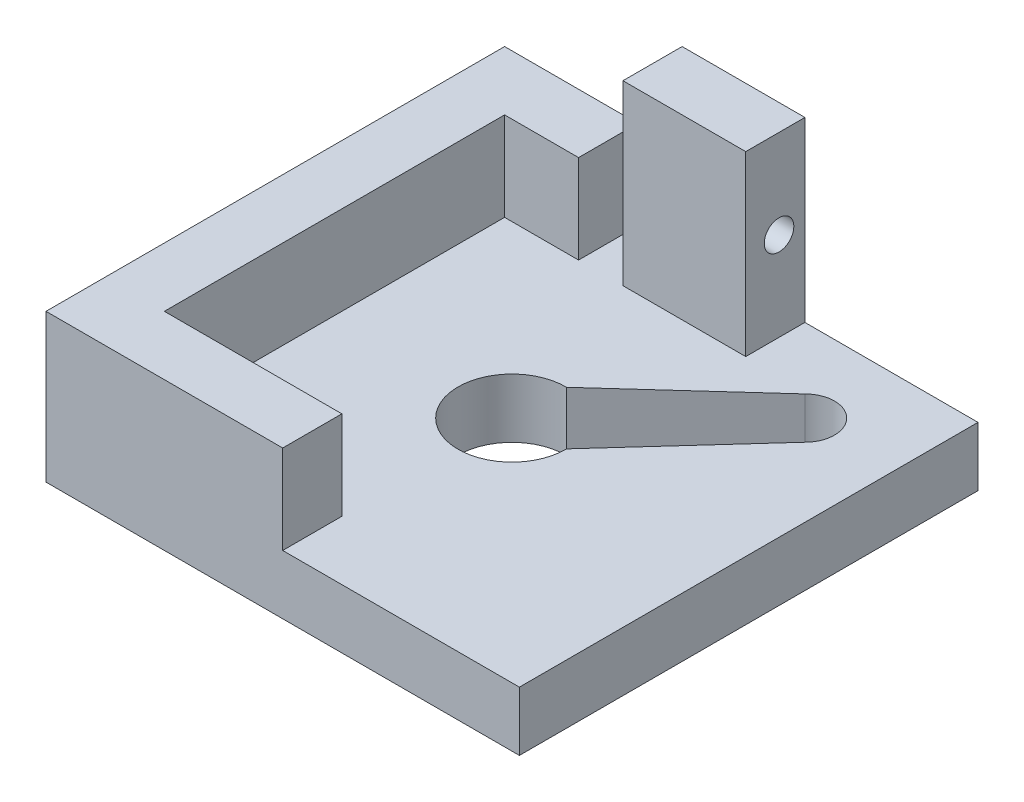
SolidWorks part; units mm, degrees
ref_plane "Front Plane" through (0, 0, 0) normal (0, 0, 1) x (1, 0, 0)
ref_plane "Top Plane" through (0, 0, 0) normal (0, 1, 0) x (1, 0, 0)
ref_plane "Right Plane" through (0, 0, 0) normal (1, 0, 0) x (0, 0, -1)
sketch "Sketch1" plane through (0, 0, 0) normal (0, 1, 0) x (1, 0, 0)
  line L1 (-16, -15.5) -> (16, -15.5)
  line L2 (-16, -15.5) -> (-16, 15.5)
  line L3 (-16, 15.5) -> (16, 15.5)
  line L4 (16, -15.5) -> (16, 15.5)
  line L5 (-16, -15.5) -> (16, 15.5) construction
  line L6 (-16, 15.5) -> (16, -15.5) construction
  point P0 (0, 0)
  dimension "D1" = 32
  dimension "D2" = 31
extrude "Boss-Extrude1" add sketch "Sketch1" along normal blind 4
sketch "Sketch2" plane through (0, 4, 0) normal (0, 1, 0) x (1, 0, 0)
  line L0 (-16, 15.5) -> (-16, -15.5)
  line L1 (-16, -15.5) -> (0, -15.5)
  line L2 (-16, -15.5) -> (16, -15.5) construction
  line L3 (0, -15.5) -> (0, -11.5)
  line L7 (-7, 11.5) -> (-12, 11.5)
  line L8 (-12, 11.5) -> (-12, -11.5)
  line L9 (-12, -11.5) -> (0, -11.5)
  line L10 (-16, 15.5) -> (-7, 15.5)
  line L11 (16, 15.5) -> (-16, 15.5) construction
  line L12 (-7, 15.5) -> (-7, 11.5)
  dimension "D1" = 4
  dimension "D2" = 4
  dimension "D3" = 5
  dimension "D4" = 4
  dimension "D5" = 31
  dimension "D6" = 9
  dimension "D7" = 16
extrude "Boss-Extrude2" add sketch "Sketch2" along normal blind 6
sketch "Sketch5" plane through (0, 4, 0) normal (0, 1, 0) x (1, 0, 0)
  line L0 (16, 15.5) -> (-7, 15.5) construction
  line L1 (-4, 11.5) -> (4.3, 11.5)
  line L2 (-4, 11.5) -> (-4, 15.5)
  line L3 (-4, 15.5) -> (4.3, 15.5)
  line L4 (4.3, 11.5) -> (4.3, 15.5)
  line L5 (-7, 11.5) -> (-7, 15.5) construction
  dimension "D1" = 3
  dimension "D2" = 8.3
  dimension "D3" = 4
extrude "Boss-Extrude3" add sketch "Sketch5" along normal blind 12
sketch "Sketch6" plane through (4.3, 0, 0) normal (1, 0, 0) x (0, 0, -1)
  line L0 (11.5, 16) -> (11.5, 4) construction
  line L2 (11.5, 16) -> (15.5, 16) construction
  circle A0 centre (13.75, 10) radius 1
  point P4 (0, 0)
  point P6 (13.7608, 16)
  dimension "D1" = 2
  dimension "D2" = 2.25
  dimension "D3" = 6
extrude "Cut-Extrude7" cut sketch "Sketch6" against normal blind 5
sketch "Sketch4" plane through (0, 4, 0) normal (0, 1, 0) x (0.7071, 0, -0.7071)
  line L0 (0, 0) -> (0, 2.55) construction
  line L1 (0, 0) -> (0, -2.55) construction
  line L2 (0, 0) -> (16, 0) construction
  line L4 (0, -2.55) -> (2.6115, -2.55) construction
  line L5 (2.6115, 2.55) -> (14, 2)
  line L7 (0, 2.55) -> (2.6115, 2.55) construction
  line L10 (16, 0) -> (14, 2) construction
  line L11 (16, 0) -> (14, -2) construction
  line L12 (2.6115, -2.55) -> (14, -2)
  circle A0 centre (0, 0) radius 3.65
  arc A3 (2.6115, 2.55) -> (2.6115, -2.55) centre (0, 0) cw
  arc A4 (16, 0) -> (14, 2) centre (14, 0) ccw
  arc A5 (16, 0) -> (14, -2) centre (14, 0) cw
  dimension "D1" = 7.3
  dimension "D2" = 16
  dimension "D3" = 45
  dimension "D4" = 45
  dimension "D5" = 2
  dimension "D6" = 2.55
  dimension "D7" = 2.55
  dimension "D8" = 2
extrude "Cut-Extrude6" cut sketch "Sketch4" against normal blind 4
